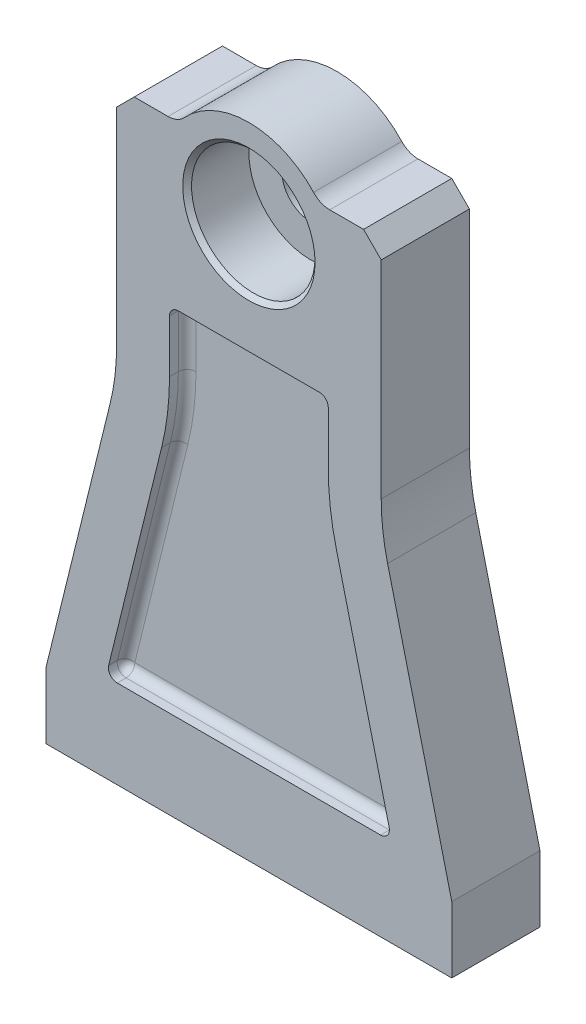
SolidWorks part; units mm, degrees
ref_plane "Front Plane" through (0, 0, 0) normal (0, 0, 1) x (1, 0, 0)
ref_plane "Top Plane" through (0, 0, 0) normal (0, 1, 0) x (1, 0, 0)
ref_plane "Right Plane" through (0, 0, 0) normal (1, 0, 0) x (0, 0, -1)
sketch "Sketch2" plane through (0, 0, 0) normal (0, 0, 1) x (1, 0, 0)
  line L0 (16, 64.5) -> (30, 64.5)
  line L1 (-46, -72.5) -> (46, -72.5)
  line L5 (-46, -72.5) -> (46, 72.5) construction
  line L6 (-46, 72.5) -> (46, -72.5) construction
  line L7 (-30, 64.5) -> (-16, 64.5)
  line L8 (-30, 64.5) -> (-30, 7.5)
  line L10 (30, 64.5) -> (30, 7.5)
  line L11 (-46, -72.5) -> (-46, -57.5)
  line L12 (-46, -57.5) -> (-30, 7.5)
  line L13 (46, -72.5) -> (46, -57.5)
  line L14 (46, -57.5) -> (30, 7.5)
  arc A1 (16, 64.5) -> (-16, 64.5) centre (0, 52.5) ccw
  point P2 (0, 0)
  point P9 (0, 0)
  point P10 (0, 0)
  point P17 (0, -72.5)
  dimension "D1" = 92
  dimension "D6" = 15
  dimension "D8" = 20
  dimension "D2" = 12
  dimension "D3" = 125
  dimension "D5" = 60
  dimension "D7" = 65
  dimension "D9" = 72.5
extrude "Boss-Extrude1" add sketch "Sketch2" along normal mid plane 20
fillet "Fillet1" radius 50 1 edges at (-30, 7.5, 0)
fillet "Fillet2" radius 50 1 edges at (30, 7.5, 0)
sketch "Sketch5" plane through (0, 0, 10) normal (0, 0, 1) x (1, 0, 0)
  line L110 (-19.7971, -1.2558) -> (-34.3478, -60.3682)
  line L111 (-18, 64.5) -> (-18, 13.5633)
  line L112 (-19.7971, -1.2558) -> (-31.801, -50.022)
  line L113 (-18, 25.5) -> (-18, 13.5633)
  line L115 (18, 13.5633) -> (18, 64.5)
  line L116 (18, 13.5633) -> (18, 25.5)
  line L118 (34.3478, -60.3682) -> (19.7971, -1.2558)
  line L119 (31.801, -50.022) -> (19.7971, -1.2558)
  line L120 (-16, 27.5) -> (16, 27.5)
  line L121 (-46, -52.5) -> (46, -52.5)
  line L122 (-29.859, -52.5) -> (29.859, -52.5)
  line L123 (-46, -72.5) -> (46, -72.5) construction
  arc A55 (-19.7971, -1.2558) -> (-18, 13.5633) centre (-80, 13.5633) ccw
  arc A56 (-19.7971, -1.2558) -> (-18, 13.5633) centre (-80, 13.5633) ccw
  arc A57 (29.859, -52.5) -> (31.801, -50.022) centre (29.859, -50.5) ccw
  arc A58 (18, 13.5633) -> (19.7971, -1.2558) centre (80, 13.5633) ccw
  arc A59 (18, 13.5633) -> (19.7971, -1.2558) centre (80, 13.5633) ccw
  arc A60 (-29.859, -52.5) -> (-31.801, -50.022) centre (-29.859, -50.5) cw
  arc A61 (18, 25.5) -> (16, 27.5) centre (16, 25.5) ccw
  arc A62 (-16, 27.5) -> (-18, 25.5) centre (-16, 25.5) ccw
  dimension "D6" = 2
  dimension "D5" = 100
  dimension "D1" = 12
  dimension "D2" = 12
  dimension "D3" = 12
  dimension "D4" = 20
extrude "Cut-Extrude1" cut sketch "Sketch5" against normal blind 4
mirror "Mirror1" about plane through (0, 0, 0) normal (0, 0, 1) of "Cut-Extrude1"
sketch "Sketch6" plane through (0, 0, 10) normal (0, 0, 1) x (1, 0, 0)
  circle A0 centre (0, 52.5) radius 6.5
extrude "Cut-Extrude2" cut sketch "Sketch6" against normal through all
sketch "Sketch7" plane through (0, 0, 10) normal (0, 0, 1) x (1, 0, 0)
  circle A0 centre (0, 52.5) radius 14
extrude "Cut-Extrude3" cut sketch "Sketch7" against normal blind 14
chamfer "Chamfer1" distance 4 angle 45 2 edges at (30, 64.5, 0) (-30, 64.5, 0)
fillet "Fillet3" radius 5 2 edges at (16, 64.5, 0) (-16, 64.5, 0)
hole_wizard "Tap Drill for M10x1.25 Tap1" positions "Sketch9" profile "Sketch10" hole size "M10x1.25" standard "ANSI Metric"
sketch "Sketch9" plane through (0, -72.5, 0) normal (0, -1, 0) x (-1, 0, 0)
  point P0 (30, 0)
  point P2 (-30, 0)
  dimension "D1" = 30
  dimension "D2" = 60
sketch "Sketch10" plane through (-30, -72.5, 0) normal (1, 0, 0) x (0, 0, -1)
  line L0 (0, 0) -> (0, 24.4)
  line L1 (0, 24.4) -> (4.4, 20)
  line L2 (4.4, 20) -> (4.4, 0)
  line L5 (4.4, 0) -> (0, 0)
  line L10 (0, 24.4) -> (-4.4, 20) construction
  line L11 (0, -6.35) -> (0, 107.95) construction
  dimension "Hole Dia." = 8.8
  dimension "Hole Depth" = 20
  dimension "Drill Angle" = 90
chamfer "Chamfer2" distance 1 angle 45 1 edges at (14, 52.5, 10)
fillet "Fillet4" radius 2 24 edges at (25.7991, -25.6389, -6) (18.4509, 6.0995, -6) (18, 19.5317, -6) (17.4142, 26.9142, -6) (0, 27.5, -6) (-17.4142, 26.9142, -6) (-18, 19.5317, -6) (-18.4509, 6.0995, -6) (-25.7991, -25.6389, -6) (-31.4332, -51.7337, -6) (0, -52.5, -6) (31.4332, -51.7337, -6) (0, -52.5, 6) (-31.4332, -51.7337, 6) (-25.7991, -25.6389, 6) (-18.4509, 6.0995, 6) (-18, 19.5317, 6) (-17.4142, 26.9142, 6) (0, 27.5, 6) (17.4142, 26.9142, 6) (18, 19.5317, 6) (18.4509, 6.0995, 6) (25.7991, -25.6389, 6) (31.4332, -51.7337, 6)
